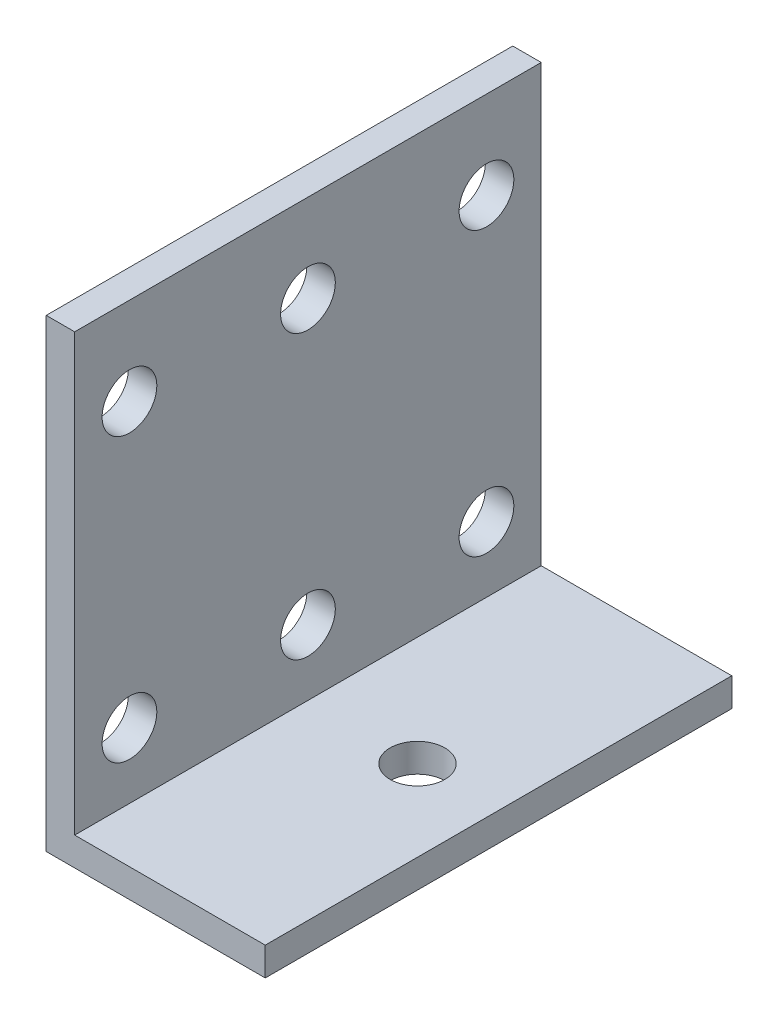
SolidWorks part; units mm, degrees
ref_plane "Front Plane" through (0, 0, 0) normal (0, 0, 1) x (1, 0, 0)
ref_plane "Top Plane" through (0, 0, 0) normal (0, 1, 0) x (1, 0, 0)
ref_plane "Right Plane" through (0, 0, 0) normal (1, 0, 0) x (0, 0, -1)
sketch "Sketch2" plane through (0, 0, 0) normal (0, 1, 0) x (1, 0, 0)
  line L1 (-12.7, -27.051) -> (12.7, -27.051)
  line L2 (-12.7, -27.051) -> (-12.7, 27.051)
  line L3 (-12.7, 27.051) -> (12.7, 27.051)
  line L4 (12.7, -27.051) -> (12.7, 27.051)
  line L5 (-12.7, -27.051) -> (12.7, 27.051) construction
  line L6 (-12.7, 27.051) -> (12.7, -27.051) construction
  point P0 (0, 0)
  point P6 (0, 0)
  dimension "D1" = 54.102
  dimension "D2" = 25.4
extrude "Boss-Extrude1" add sketch "Sketch2" along normal blind 3.302
sketch "Sketch3" plane through (0, 3.302, 0) normal (0, 1, 0) x (1, 0, 0)
  line L0 (-12.7, -27.051) -> (12.7, -27.051) construction
  line L2 (-12.7, 27.051) -> (-9.398, 27.051)
  line L3 (-12.7, 27.051) -> (-12.7, -27.051)
  line L4 (-12.7, -27.051) -> (-9.398, -27.051)
  line L5 (-9.398, 27.051) -> (-9.398, -27.051)
  dimension "D1" = 3.302
extrude "Boss-Extrude2" add sketch "Sketch3" along normal blind 50.546 contours L5 L4 L3 L2
hole_wizard "1/4 (0.25) Diameter Hole1" positions "Sketch5" profile "Sketch7" hole size "1/4" standard "ANSI Inch" end condition through all
sketch "Sketch5" plane through (-9.398, 0, 0) normal (1, 0, 0) x (0, 0, -1)
  line L1 (-20.701, 43.6857) -> (20.701, 43.6857) construction
  line L2 (-20.701, 43.6857) -> (-20.701, 10.9095) construction
  line L3 (-20.701, 10.9095) -> (20.701, 10.9095) construction
  line L4 (20.701, 43.6857) -> (20.701, 10.9095) construction
  line L7 (27.051, 53.848) -> (-27.051, 53.848) construction
  line L8 (-27.051, 53.848) -> (-27.051, 3.302) construction
  line L9 (27.051, 53.848) -> (27.051, 3.302) construction
  point P0 (-20.701, 43.6857)
  point P2 (0, 43.6857)
  point P4 (20.701, 43.6857)
  point P6 (20.701, 10.9095)
  point P8 (0, 10.9095)
  point P10 (-20.701, 10.9095)
  point P155 (-21.2591, 44.8722)
  point P156 (-0.1993, 44.8722)
  point P157 (0, 0)
  point P158 (20.3415, 45.4654)
  point P159 (20.8606, 44.8722)
  point P160 (20.8606, 12.096)
  point P161 (-0.1993, 12.096)
  point P162 (-21.2591, 12.096)
  point P167 (0, 0)
  point P168 (0, 0)
  point P174 (0, 0)
  dimension "D1" = 32.7762
  dimension "D2" = 6.35
  dimension "D3" = 6.35
  dimension "D4" = 10.1623
sketch "Sketch7" plane through (-9.398, 43.6857, 20.701) normal (0, 1, 0) x (0, 0, -1)
  line L0 (0, 0) -> (0, 3.302)
  line L1 (0, 3.302) -> (3.175, 3.302)
  line L2 (3.175, 3.302) -> (3.175, 0)
  line L5 (3.175, 0) -> (0, 0)
  line L11 (0, -6.35) -> (0, 107.95) construction
  dimension "Thru Hole Dia." = 6.35
  dimension "Thru Hole Depth" = 3.302
sketch "Sketch8" plane through (0, 3.302, 0) normal (0, 1, 0) x (1, 0, 0)
  line L0 (12.7, -27.051) -> (12.7, 27.051) construction
  line L1 (-9.398, 0) -> (12.7, 0)
  line L2 (-9.398, 27.051) -> (-9.398, -27.051) construction
  point P6 (3.302, 0)
  dimension "D1" = 12.7
hole_wizard "1/4 (0.25) Diameter Hole3" positions "Sketch9" profile "Sketch10" hole size "1/4" standard "ANSI Inch" end condition through all
sketch "Sketch9" plane through (0, 3.302, 0) normal (0, 1, 0) x (1, 0, 0)
  point P0 (3.302, 0)
sketch "Sketch10" plane through (3.302, 3.302, 0) normal (1, 0, 0) x (0, 0, 1)
  line L0 (0, 0) -> (0, 3.302)
  line L1 (0, 3.302) -> (3.175, 3.302)
  line L2 (3.175, 3.302) -> (3.175, 0)
  line L5 (3.175, 0) -> (0, 0)
  line L11 (0, -6.35) -> (0, 107.95) construction
  dimension "Thru Hole Dia." = 6.35
  dimension "Thru Hole Depth" = 3.302
